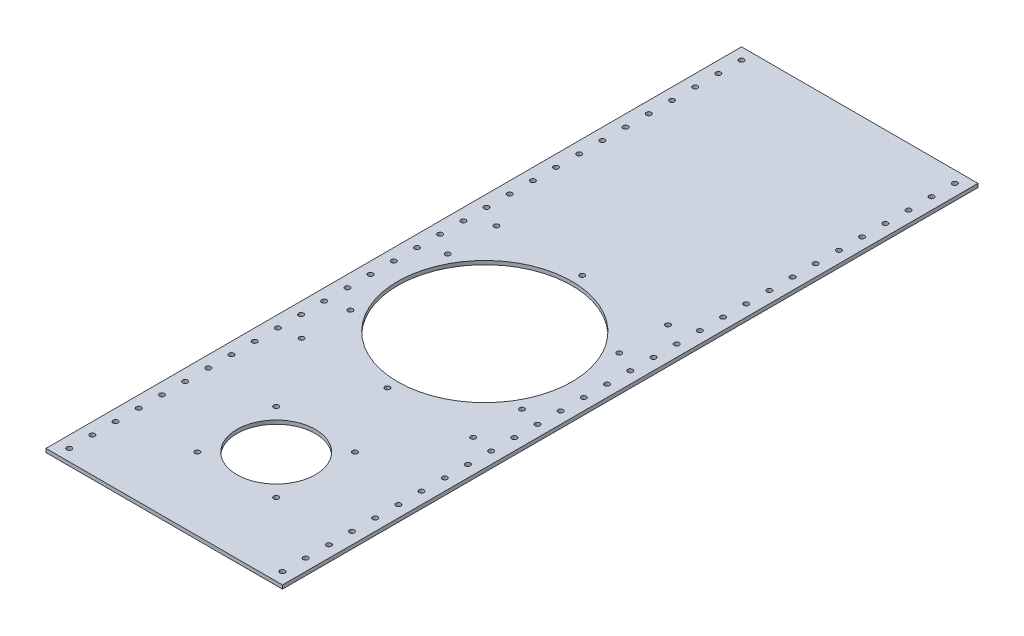
SolidWorks part; units mm, degrees
ref_plane "Front Plane" through (0, 0, 0) normal (0, 0, 1) x (1, 0, 0)
ref_plane "Top Plane" through (0, 0, 0) normal (0, 1, 0) x (1, 0, 0)
ref_plane "Right Plane" through (0, 0, 0) normal (1, 0, 0) x (0, 0, -1)
sketch "Sketch1" plane through (0, 0, 0) normal (0, 1, 0) x (1, 0, 0)
  line L0 (0, 250) -> (0, -350) construction
  line L1 (-102, -350) -> (102, -350)
  line L2 (-102, -350) -> (-102, 250)
  line L3 (-102, 250) -> (102, 250)
  line L4 (102, -350) -> (102, 250)
  line L5 (-102, -350) -> (102, 250) construction
  line L6 (-102, 250) -> (102, -350) construction
  line L7 (-102, -73.451) -> (102, -73.451) construction
  line L8 (92, 250) -> (92, -350) construction
  line L9 (-92, 250) -> (-92, -350) construction
  line L10 (-40, -253.451) -> (40, -253.451) construction
  line L11 (-80, -163.451) -> (80, -163.451) construction
  line L12 (-80, -163.451) -> (-80, 16.549) construction
  line L13 (-80, 16.549) -> (80, 16.549) construction
  line L14 (80, -163.451) -> (80, 16.549) construction
  line L15 (-80, -163.451) -> (80, 16.549) construction
  line L16 (-80, 16.549) -> (80, -163.451) construction
  line L17 (-40, -293.451) -> (40, -293.451) construction
  line L18 (-40, -293.451) -> (-40, -213.451) construction
  line L19 (-40, -213.451) -> (40, -213.451) construction
  line L20 (40, -293.451) -> (40, -213.451) construction
  line L21 (-40, -293.451) -> (40, -213.451) construction
  line L22 (-40, -213.451) -> (40, -293.451) construction
  circle A232 centre (92, 240) radius 2.15
  circle A233 centre (92, 220) radius 2.15
  circle A234 centre (92, 200) radius 2.15
  circle A235 centre (92, 180) radius 2.15
  circle A236 centre (92, 160) radius 2.15
  circle A237 centre (92, 140) radius 2.15
  circle A238 centre (92, 120) radius 2.15
  circle A239 centre (92, 100) radius 2.15
  circle A240 centre (92, 80) radius 2.15
  circle A241 centre (92, 60) radius 2.15
  circle A242 centre (92, 40) radius 2.15
  circle A243 centre (92, 20) radius 2.15
  circle A244 centre (92, 0) radius 2.15
  circle A245 centre (92, -20) radius 2.15
  circle A246 centre (92, -40) radius 2.15
  circle A247 centre (92, -60) radius 2.15
  circle A248 centre (92, -80) radius 2.15
  circle A249 centre (92, -100) radius 2.15
  circle A250 centre (92, -120) radius 2.15
  circle A251 centre (92, -140) radius 2.15
  circle A252 centre (92, -160) radius 2.15
  circle A253 centre (92, -180) radius 2.15
  circle A254 centre (92, -200) radius 2.15
  circle A255 centre (92, -220) radius 2.15
  circle A256 centre (92, -240) radius 2.15
  circle A257 centre (92, -260) radius 2.15
  circle A258 centre (92, -280) radius 2.15
  circle A259 centre (92, -300) radius 2.15
  circle A260 centre (92, -320) radius 2.15
  circle A261 centre (92, -340) radius 2.15
  circle A262 centre (-92, -340) radius 2.15
  circle A263 centre (-92, -320) radius 2.15
  circle A264 centre (-92, -300) radius 2.15
  circle A265 centre (-92, -280) radius 2.15
  circle A266 centre (-92, -260) radius 2.15
  circle A267 centre (-92, -240) radius 2.15
  circle A268 centre (-92, -220) radius 2.15
  circle A269 centre (-92, -200) radius 2.15
  circle A270 centre (-92, -180) radius 2.15
  circle A271 centre (-92, -160) radius 2.15
  circle A272 centre (-92, -140) radius 2.15
  circle A273 centre (-92, -120) radius 2.15
  circle A274 centre (-92, -100) radius 2.15
  circle A275 centre (-92, -80) radius 2.15
  circle A276 centre (-92, -60) radius 2.15
  circle A277 centre (-92, -40) radius 2.15
  circle A278 centre (-92, -20) radius 2.15
  circle A279 centre (-92, 0) radius 2.15
  circle A280 centre (-92, 20) radius 2.15
  circle A281 centre (-92, 40) radius 2.15
  circle A282 centre (-92, 60) radius 2.15
  circle A283 centre (-92, 80) radius 2.15
  circle A284 centre (-92, 100) radius 2.15
  circle A285 centre (-92, 120) radius 2.15
  circle A286 centre (-92, 140) radius 2.15
  circle A287 centre (-92, 160) radius 2.15
  circle A288 centre (-92, 180) radius 2.15
  circle A289 centre (-92, 200) radius 2.15
  circle A290 centre (-92, 220) radius 2.15
  circle A291 centre (-92, 240) radius 2.15
  circle A292 centre (0, -73.451) radius 62.5 construction
  circle A293 centre (-74, -157.451) radius 2.125
  circle A294 centre (-74, -115.451) radius 2.125
  circle A296 centre (0, -157.451) radius 2.125
  circle A297 centre (74, -157.451) radius 2.125
  circle A298 centre (74, -115.451) radius 2.125
  circle A299 centre (74, -31.451) radius 2.125
  circle A300 centre (74, 10.549) radius 2.125
  circle A301 centre (0, 10.549) radius 2.125
  circle A302 centre (-74, 10.549) radius 2.125
  circle A303 centre (-74, -31.451) radius 2.125
  circle A304 centre (0, -253.451) radius 33.85
  circle A310 centre (0, -73.451) radius 75.125
  circle A313 centre (-34, -287.451) radius 2.15
  circle A314 centre (34, -287.451) radius 2.15
  circle A315 centre (34, -219.451) radius 2.15
  circle A316 centre (-34, -219.451) radius 2.15
  point P175 (0, -253.451)
  dimension "D3" = 10
  dimension "D8" = 180
  dimension "D9" = 4.25
  dimension "D11" = 6
  dimension "D16" = 150.25
  dimension "D17" = 4.25
  dimension "D19" = 180
  dimension "D21" = 80
  dimension "D4" = 4.3
  dimension "D6" = 125
  dimension "D13" = 4.25
  dimension "D20" = 80
  dimension "D22" = 67.7
  dimension "D23" = 73.451
  dimension "D25" = 4.3
  dimension "D2" = 600
  dimension "D5" = 10
  dimension "D7" = 160
  dimension "D12" = 42
  dimension "D15" = 276.549
  dimension "D18" = 6
  dimension "D24" = 204
  dimension "D10" = 6
  dimension "D14" = 0
  dimension "D26" = 6
  dimension "D27" = 6
extrude "Boss-Extrude1" add sketch "Sketch1" along normal blind 3.175
equation "\"m3\"=3.2"
